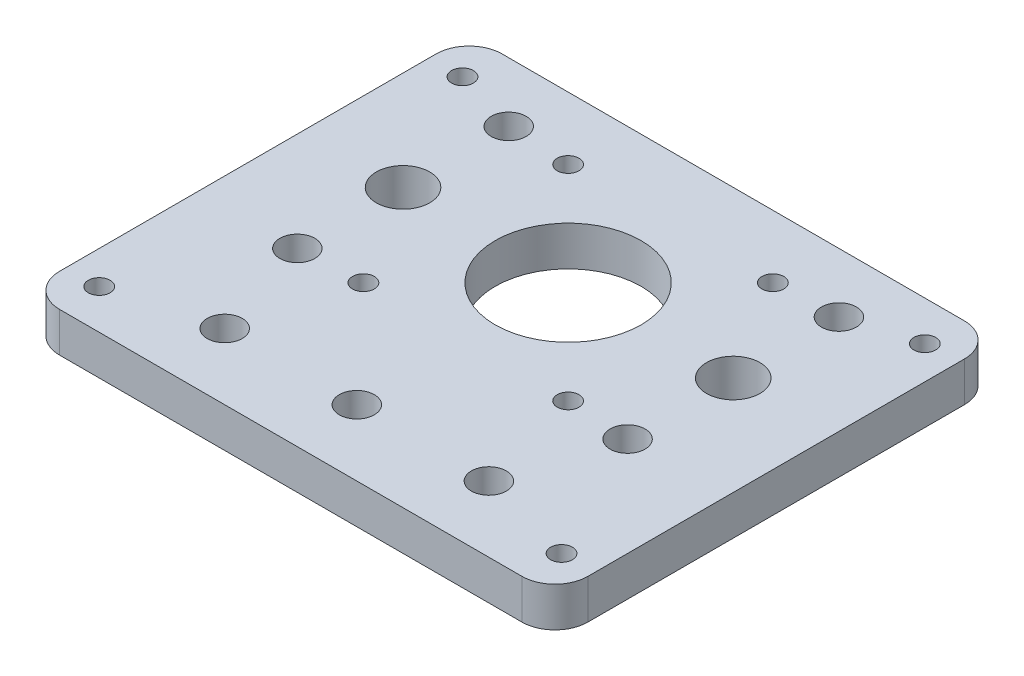
SolidWorks part; units mm, degrees
ref_plane "前视基准面" through (0, 0, 0) normal (0, 0, 1) x (1, 0, 0)
ref_plane "上视基准面" through (0, 0, 0) normal (0, 1, 0) x (1, 0, 0)
ref_plane "右视基准面" through (0, 0, 0) normal (1, 0, 0) x (0, 0, -1)
sketch "草图1" plane through (0, 0, 0) normal (0, 1, 0) x (1, 0, 0)
  line L0 (0, 80.3703) -> (0, -68.6055) construction
  line L1 (-122.6133, 0) -> (117.4549, 0) construction
  line L2 (-122.6133, -15.5) -> (117.4549, -15.5) construction
  line L3 (-15.5, 80.3703) -> (-15.5, -68.6055) construction
  line L4 (-122.6133, 15.5) -> (117.4549, 15.5) construction
  line L5 (15.5, 80.3703) -> (15.5, -68.6055) construction
  line L6 (-21.2, 80.3703) -> (-21.2, -68.6055) construction
  line L7 (21.2, 80.3703) -> (21.2, -68.6055) construction
  line L8 (-122.6133, -21.2) -> (117.4549, -21.2) construction
  line L9 (-122.6133, 21.2) -> (117.4549, 21.2) construction
  line L10 (-25, 80.3703) -> (-25, -68.6055) construction
  line L11 (25, 80.3703) -> (25, -68.6055) construction
  line L12 (-122.6133, -16) -> (117.4549, -16) construction
  line L13 (-122.6133, 16) -> (117.4549, 16) construction
  line L14 (-122.6133, -21.5) -> (117.4549, -21.5) construction
  line L15 (-122.6133, 21.5) -> (117.4549, 21.5) construction
  line L16 (-122.6133, -32) -> (117.4549, -32) construction
  line L17 (-122.6133, 32) -> (117.4549, 32) construction
  line L18 (-20, 80.3703) -> (-20, -68.6055) construction
  line L19 (20, 80.3703) -> (20, -68.6055) construction
  line L20 (-35, -42) -> (35, -42)
  line L21 (-122.6133, -22) -> (117.4549, -22) construction
  line L22 (-40, 20) -> (-40, -37)
  line L23 (40, 20) -> (40, -37)
  line L24 (-35, 25) -> (35, 25)
  line L25 (-40, 80.3703) -> (-40, -68.6055) construction
  line L26 (-122.6133, -42) -> (117.4549, -42) construction
  line L27 (40, 80.3703) -> (40, -68.6055) construction
  line L28 (-122.6133, 25) -> (117.4549, 25) construction
  line L29 (-35, 80.3703) -> (-35, -68.6055) construction
  circle A0 centre (0, 0) radius 11.05
  circle A3 centre (-15.5, 15.5) radius 1.65
  circle A4 centre (15.5, 15.5) radius 1.65
  circle A5 centre (15.5, -15.5) radius 1.65
  circle A6 centre (-15.5, -15.5) radius 1.65
  circle A7 centre (-25, 0) radius 4.05
  circle A8 centre (-25, 16) radius 2.65
  circle A9 centre (-25, -16) radius 2.65
  circle A10 centre (25, 0) radius 4.05
  circle A11 centre (25, -16) radius 2.65
  circle A12 centre (25, 16) radius 2.65
  circle A13 centre (-20, -32) radius 2.65
  circle A14 centre (0, -32) radius 2.65
  circle A15 centre (20, -32) radius 2.65
  arc A16 (-40, -37) -> (-35, -42) centre (-35, -37) ccw
  arc A17 (35, -42) -> (40, -37) centre (35, -37) ccw
  arc A18 (40, 20) -> (35, 25) centre (35, 20) ccw
  arc A19 (-35, 25) -> (-40, 20) centre (-35, 20) ccw
  circle A20 centre (-35, 19) radius 1.65
  circle A21 centre (-35, -36) radius 1.65
  circle A22 centre (35, -36) radius 1.65
  circle A23 centre (35, 19) radius 1.65
  point P26 (0, 0)
  point P95 (-35, 19)
  point P96 (-35, -36)
  point P104 (-35, -36)
  point P105 (0, 0)
  dimension "D1" = 22.1
  dimension "D2" = 15.5
  dimension "D4" = 3.3
  dimension "D5" = 4
  dimension "D12" = 8.1
  dimension "D15" = 5.3
  dimension "D22" = 5.3
  dimension "D29" = 5
  dimension "D34" = 3.3
  dimension "D31" = 6
  dimension "D32" = 6
  dimension "D3" = 15.5
  dimension "D6" = 21.2
  dimension "D7" = 21.2
  dimension "D8" = 21.2
  dimension "D9" = 21.2
  dimension "D10" = 25
  dimension "D11" = 25
  dimension "D13" = 16
  dimension "D14" = 16
  dimension "D16" = 21.5
  dimension "D17" = 21.5
  dimension "D18" = 32
  dimension "D19" = 32
  dimension "D20" = 20
  dimension "D21" = 20
  dimension "D24" = 10
  dimension "D25" = 10
  dimension "D26" = 40
  dimension "D27" = 40
  dimension "D28" = 25
  dimension "D30" = 35
  dimension "D23" = 3
extrude "凸台-拉伸1" add sketch "草图1" along normal blind 6
